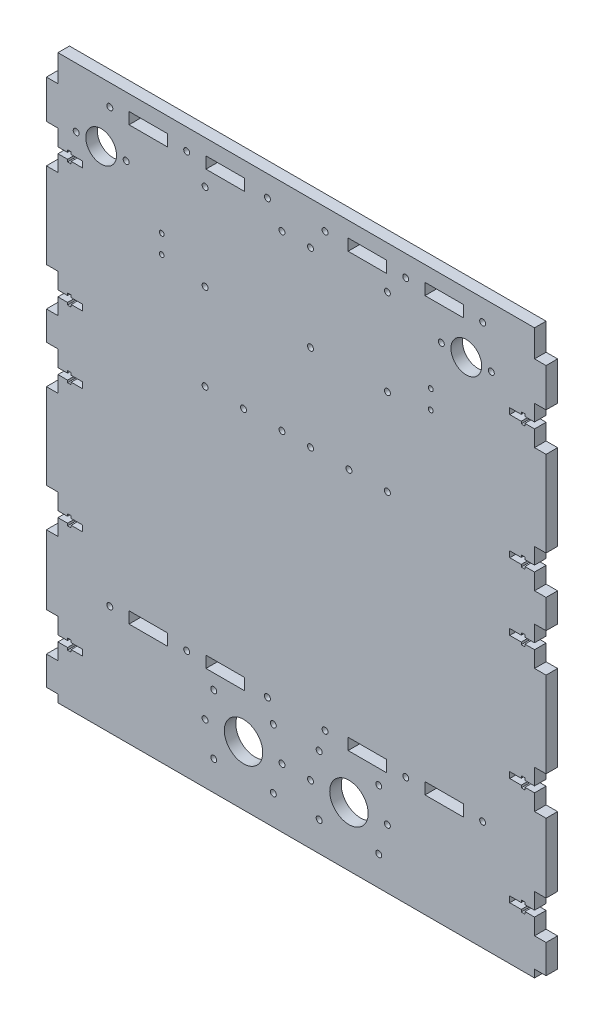
SolidWorks part; units mm, degrees
ref_plane "Front Plane" through (0, 0, 0) normal (0, 0, 1) x (1, 0, 0)
ref_plane "Top Plane" through (0, 0, 0) normal (0, 1, 0) x (1, 0, 0)
ref_plane "Right Plane" through (0, 0, 0) normal (1, 0, 0) x (0, 0, -1)
sketch "Sketch1" plane through (0, 0, 0) normal (0, 0, 1) x (1, 0, 0)
  line L1 (0, 0) -> (260, 0)
  line L2 (0, 0) -> (0, 270)
  line L3 (0, 270) -> (260, 270)
  line L4 (260, 0) -> (260, 270)
  dimension "D1" = 270
  dimension "D2" = 260
extrude "Boss-Extrude1" add sketch "Sketch1" along normal blind 6
sketch "Sketch2" plane through (0, 0, 0) normal (0, 0, -1) x (-1, 0, 0)
  line L0 (-130, 270) -> (-130, 0) construction
  line L1 (-217, 56) -> (-197, 56)
  line L2 (-217, 56) -> (-217, 50)
  line L3 (-217, 50) -> (-197, 50)
  line L4 (-197, 56) -> (-197, 50)
  line L5 (-177, 56) -> (-157, 56)
  line L6 (-177, 56) -> (-177, 50)
  line L7 (-177, 50) -> (-157, 50)
  line L8 (-157, 56) -> (-157, 50)
  line L9 (-260, 270) -> (0, 270) construction
  line L10 (0, 0) -> (-260, 0) construction
  line L11 (-260, 0) -> (-260, 270) construction
  line L12 (-217, 53) -> (-157, 53) construction
  line L13 (-130, 0) -> (-130, -73.8705) construction
  line L14 (-130, -73.8705) -> (-130, -196.098) construction
  line L16 (-220, 0) -> (-40, 0)
  line L17 (-83, 50) -> (-103, 50)
  line L18 (-103, 56) -> (-103, 50)
  line L19 (-83, 56) -> (-103, 56)
  line L20 (-83, 56) -> (-83, 50)
  line L21 (-43, 50) -> (-63, 50)
  line L22 (-63, 56) -> (-63, 50)
  line L23 (-43, 56) -> (-63, 56)
  line L24 (-43, 56) -> (-43, 50)
  arc A0 (-220, 0) -> (-40, 0) centre (-130, -400) cw
  point P23 (-130, 10)
  point P26 (-130, 10)
  dimension "D9" = 40
  dimension "D1" = 43
  dimension "D2" = 20
  dimension "D3" = 20
  dimension "D4" = 20
  dimension "D5" = 6
  dimension "D6" = 6
  dimension "D7" = 50
  dimension "D8" = 3
  dimension "D12" = 10
extrude "Cut-Extrude1" cut sketch "Sketch2" against normal blind 6
sketch "Sketch3" plane through (0, 0, 0) normal (0, 0, -1) x (-1, 0, 0)
  line L2 (-260, 255) -> (-260, 235)
  line L4 (-254, 255) -> (-254, 235)
  line L5 (-197, 56) -> (-217, 56) construction
  line L6 (-260, 255) -> (-254, 255)
  line L7 (-260, 255) -> (-260, 235)
  line L8 (-260, 235) -> (-254, 235)
  line L9 (-254, 255) -> (-254, 235)
  line L10 (-260, 190.5) -> (-254, 190.5)
  line L11 (-260, 190.5) -> (-260, 170.5)
  line L12 (-260, 170.5) -> (-254, 170.5)
  line L13 (-254, 190.5) -> (-254, 170.5)
  line L14 (-254, 155.5) -> (-260, 155.5)
  line L15 (-254, 155.5) -> (-254, 135.5)
  line L16 (-254, 135.5) -> (-260, 135.5)
  line L17 (-260, 155.5) -> (-260, 135.5)
  line L18 (-260, 91) -> (-254, 91)
  line L19 (-260, 91) -> (-260, 71)
  line L20 (-260, 71) -> (-254, 71)
  line L21 (-254, 91) -> (-254, 71)
  line L22 (-260, 35) -> (-254, 35)
  line L23 (-260, 35) -> (-260, 15)
  line L24 (-260, 15) -> (-254, 15)
  line L25 (-254, 35) -> (-254, 15)
  line L27 (-254, 190.5) -> (-254, 170.5)
  line L28 (-260, 190.5) -> (-260, 170.5)
  line L29 (-260, 155.5) -> (-260, 135.5)
  line L30 (-254, 155.5) -> (-254, 135.5)
  line L31 (-254, 91) -> (-254, 71)
  line L32 (-260, 91) -> (-260, 71)
  line L33 (-260, 35) -> (-260, 15)
  line L34 (-254, 35) -> (-254, 15)
  line L35 (-254, 270) -> (-254, 0) construction
  line L36 (-260, 270) -> (0, 270) construction
  line L37 (-220, 0) -> (-260, 0) construction
  line L38 (-260, 0) -> (-260, 270) construction
  line L39 (-130, 270) -> (-130, 0) construction
  line L40 (0, 15) -> (-6, 15)
  line L41 (-6, 35) -> (-6, 15)
  line L42 (0, 35) -> (-6, 35)
  line L43 (0, 35) -> (0, 15)
  line L44 (0, 71) -> (-6, 71)
  line L45 (-6, 91) -> (-6, 71)
  line L46 (0, 91) -> (-6, 91)
  line L47 (0, 91) -> (0, 71)
  line L48 (-6, 135.5) -> (0, 135.5)
  line L49 (0, 155.5) -> (0, 135.5)
  line L50 (-6, 155.5) -> (0, 155.5)
  line L51 (-6, 155.5) -> (-6, 135.5)
  line L52 (0, 170.5) -> (-6, 170.5)
  line L53 (-6, 190.5) -> (-6, 170.5)
  line L54 (0, 190.5) -> (-6, 190.5)
  line L55 (0, 190.5) -> (0, 170.5)
  line L56 (0, 235) -> (-6, 235)
  line L57 (-6, 255) -> (-6, 235)
  line L58 (0, 255) -> (-6, 255)
  line L59 (0, 255) -> (0, 235)
  point P27 (-257, 170.5)
  point P28 (-257, 155.5)
  point P29 (-257, 71)
  line M33 (0, 0) -> (0, 270)
  line M35 (-260, 270) -> (-260, 0)
  dimension "D1" = 6
  dimension "D2" = 20
  dimension "D3" = 20
  dimension "D4" = 20
  dimension "D5" = 20
  dimension "D6" = 20
  dimension "D7" = 6
  dimension "D8" = 15
  dimension "D9" = 44.5
  dimension "D10" = 15
  dimension "D11" = 44.5
extrude "Cut-Extrude2" cut sketch "Sketch3" against normal blind 10 contours L8 L4 L6 M35 | L13 L10 L12 M35 | L16 L15 L14 M35 | L21 L18 L20 M35 | L25 L22 L24 M35 | L42 L41 L40 M33 | L50 L51 L48 M33 | L54 L53 L52 M33 | L58 L57 L56 M33 | L47 L44 L45 L46
sketch "Sketch4" plane through (0, 0, 6) normal (0, 0, 1) x (1, 0, 0)
  line L0 (130, 270) -> (130, 0) construction
  line L1 (260, 270) -> (0, 270) construction
  line L2 (0, 270) -> (0, 255) construction
  line L3 (260, 270) -> (0, 270) construction
  circle A0 centre (28.5, 258) radius 8
  circle A2 centre (218.5, 258) radius 8
  dimension "D1" = 16
  dimension "D4" = 16
  dimension "D2" = 12
  dimension "D3" = 28.5
  dimension "D5" = 190
  dimension "D6" = 12
extrude "Cut-Extrude3" cut sketch "Sketch4" against normal blind 10
sketch "Sketch5" plane through (0, 0, 6) normal (0, 0, 1) x (1, 0, 0)
  line L0 (28.5, 266) -> (28.5, 250) construction
  line L1 (15.5, 258) -> (28.5, 258) construction
  line L2 (130, 270) -> (130, 307.8731) construction
  line L3 (260, 270) -> (0, 270) construction
  line L4 (205.5, 258) -> (231.5, 258) construction
  circle A0 centre (28.5, 258) radius 8 construction
  circle A1 centre (28.5, 258) radius 8
  circle A2 centre (15.5, 258) radius 1.55
  circle A3 centre (41.5, 258) radius 1.55
  circle A7 centre (218.5, 258) radius 8 construction
  circle A8 centre (218.5, 258) radius 8
  circle A9 centre (205.5, 258) radius 1.55
  circle A10 centre (231.5, 258) radius 1.55
  dimension "D2" = 3.1
  dimension "D3" = 3.1
  dimension "D4" = 13
  dimension "D7" = 3.1
  dimension "D1" = 13
  dimension "D5" = 13
  dimension "D6" = 13
extrude "Cut-Extrude4" cut sketch "Sketch5" against normal blind 6
sketch "Sketch6" plane through (0, 270, 0) normal (0, 1, 0) x (1, 0, 0)
  line L4 (260, 0) -> (0, 0)
  line L5 (0, 0) -> (0, -6)
  line L6 (0, -6) -> (260, -6)
  line L7 (260, -6) -> (260, 0)
  line L8 (260, 0) -> (0, 0)
  line L9 (0, 0) -> (0, -6)
  line L10 (0, -6) -> (260, -6)
  line L11 (260, -6) -> (260, 0)
  dimension "D1" = 0
extrude "Boss-Extrude2" add sketch "Sketch6" along normal blind 5
sketch "Sketch8" plane through (0, 0, 6) normal (0, 0, 1) x (1, 0, 0)
  line L0 (130, 137.5) -> (99.5396, 137.5) construction
  line L1 (0, 275) -> (260, 275) construction
  line L2 (0, 163) -> (24.6988, 163) construction
  line L3 (12.9, 243.45) -> (12.9, 242.25)
  line L4 (0, 170.5) -> (0, 155.5) construction
  line L5 (12.9, 243.45) -> (18.9, 243.45)
  line L6 (0, 113.25) -> (22.1113, 113.25) construction
  line L7 (0, 135.5) -> (0, 91) construction
  line L8 (0, 53) -> (19.2315, 53) construction
  line L9 (0, 71) -> (0, 35) construction
  line L34 (130, 275) -> (130, 0) construction
  line L35 (0, 212.75) -> (26.3273, 212.75) construction
  line L36 (0, 235) -> (0, 190.5) construction
  line L37 (6, 255) -> (6, 235) construction
  line L38 (6, 246.55) -> (11, 246.55)
  line L39 (6, 246.55) -> (6, 243.45)
  line L40 (6, 243.45) -> (11, 243.45)
  line L41 (18.9, 246.55) -> (18.9, 243.45)
  line L42 (6, 245) -> (35.7835, 245) construction
  line L43 (12.9, 246.55) -> (18.9, 246.55)
  line L44 (0, 255) -> (6, 255) construction
  line L45 (11, 243.45) -> (11, 242.25)
  line L46 (11, 247.75) -> (12.9, 247.75)
  line L47 (11, 247.75) -> (11, 246.55)
  line L48 (11, 242.25) -> (12.9, 242.25)
  line L49 (12.9, 247.75) -> (12.9, 246.55)
  line L50 (12.9, 177.75) -> (12.9, 178.95)
  line L51 (11, 183.25) -> (12.9, 183.25)
  line L52 (11, 177.75) -> (11, 178.95)
  line L53 (11, 177.75) -> (12.9, 177.75)
  line L54 (11, 182.05) -> (11, 183.25)
  line L55 (12.9, 178.95) -> (18.9, 178.95)
  line L56 (18.9, 178.95) -> (18.9, 182.05)
  line L57 (6, 182.05) -> (11, 182.05)
  line L58 (6, 178.95) -> (6, 182.05)
  line L59 (6, 178.95) -> (11, 178.95)
  line L60 (12.9, 182.05) -> (18.9, 182.05)
  line L61 (12.9, 182.05) -> (12.9, 183.25)
  line L62 (12.9, 143.95) -> (12.9, 142.75)
  line L63 (12.9, 143.95) -> (18.9, 143.95)
  line L64 (6, 147.05) -> (11, 147.05)
  line L65 (6, 147.05) -> (6, 143.95)
  line L66 (6, 143.95) -> (11, 143.95)
  line L67 (18.9, 147.05) -> (18.9, 143.95)
  line L68 (12.9, 147.05) -> (18.9, 147.05)
  line L69 (11, 143.95) -> (11, 142.75)
  line L70 (11, 148.25) -> (12.9, 148.25)
  line L71 (11, 148.25) -> (11, 147.05)
  line L72 (11, 142.75) -> (12.9, 142.75)
  line L73 (12.9, 148.25) -> (12.9, 147.05)
  line L74 (12.9, 78.25) -> (12.9, 79.45)
  line L75 (11, 83.75) -> (12.9, 83.75)
  line L76 (11, 78.25) -> (11, 79.45)
  line L77 (11, 78.25) -> (12.9, 78.25)
  line L78 (11, 82.55) -> (11, 83.75)
  line L79 (12.9, 79.45) -> (18.9, 79.45)
  line L80 (18.9, 79.45) -> (18.9, 82.55)
  line L81 (6, 82.55) -> (11, 82.55)
  line L82 (6, 79.45) -> (6, 82.55)
  line L83 (6, 79.45) -> (11, 79.45)
  line L84 (12.9, 82.55) -> (18.9, 82.55)
  line L85 (12.9, 82.55) -> (12.9, 83.75)
  line L86 (12.9, 23.45) -> (12.9, 22.25)
  line L87 (12.9, 23.45) -> (18.9, 23.45)
  line L88 (6, 26.55) -> (11, 26.55)
  line L89 (6, 26.55) -> (6, 23.45)
  line L90 (6, 23.45) -> (11, 23.45)
  line L91 (18.9, 26.55) -> (18.9, 23.45)
  line L92 (12.9, 26.55) -> (18.9, 26.55)
  line L93 (11, 23.45) -> (11, 22.25)
  line L94 (11, 27.75) -> (12.9, 27.75)
  line L95 (11, 27.75) -> (11, 26.55)
  line L96 (11, 22.25) -> (12.9, 22.25)
  line L97 (12.9, 27.75) -> (12.9, 26.55)
  line L98 (254, 245) -> (224.2165, 245) construction
  line L99 (260, 212.75) -> (233.6727, 212.75) construction
  line L100 (260, 53) -> (240.7685, 53) construction
  line L101 (260, 113.25) -> (237.8887, 113.25) construction
  line L102 (260, 163) -> (235.3012, 163) construction
  line L103 (247.1, 27.75) -> (247.1, 26.55)
  line L104 (249, 22.25) -> (247.1, 22.25)
  line L105 (249, 27.75) -> (249, 26.55)
  line L106 (249, 27.75) -> (247.1, 27.75)
  line L107 (249, 23.45) -> (249, 22.25)
  line L108 (247.1, 26.55) -> (241.1, 26.55)
  line L109 (241.1, 26.55) -> (241.1, 23.45)
  line L110 (254, 23.45) -> (249, 23.45)
  line L111 (254, 26.55) -> (254, 23.45)
  line L112 (254, 26.55) -> (249, 26.55)
  line L113 (247.1, 23.45) -> (241.1, 23.45)
  line L114 (247.1, 23.45) -> (247.1, 22.25)
  line L115 (247.1, 82.55) -> (247.1, 83.75)
  line L116 (247.1, 82.55) -> (241.1, 82.55)
  line L117 (254, 79.45) -> (249, 79.45)
  line L118 (254, 79.45) -> (254, 82.55)
  line L119 (254, 82.55) -> (249, 82.55)
  line L120 (241.1, 79.45) -> (241.1, 82.55)
  line L121 (247.1, 79.45) -> (241.1, 79.45)
  line L122 (249, 82.55) -> (249, 83.75)
  line L123 (249, 78.25) -> (247.1, 78.25)
  line L124 (249, 78.25) -> (249, 79.45)
  line L125 (249, 83.75) -> (247.1, 83.75)
  line L126 (247.1, 78.25) -> (247.1, 79.45)
  line L127 (247.1, 148.25) -> (247.1, 147.05)
  line L128 (249, 142.75) -> (247.1, 142.75)
  line L129 (249, 148.25) -> (249, 147.05)
  line L130 (249, 148.25) -> (247.1, 148.25)
  line L131 (249, 143.95) -> (249, 142.75)
  line L132 (247.1, 147.05) -> (241.1, 147.05)
  line L133 (241.1, 147.05) -> (241.1, 143.95)
  line L134 (254, 143.95) -> (249, 143.95)
  line L135 (254, 147.05) -> (254, 143.95)
  line L136 (254, 147.05) -> (249, 147.05)
  line L137 (247.1, 143.95) -> (241.1, 143.95)
  line L138 (247.1, 143.95) -> (247.1, 142.75)
  line L139 (247.1, 182.05) -> (247.1, 183.25)
  line L140 (247.1, 182.05) -> (241.1, 182.05)
  line L141 (254, 178.95) -> (249, 178.95)
  line L142 (254, 178.95) -> (254, 182.05)
  line L143 (254, 182.05) -> (249, 182.05)
  line L144 (241.1, 178.95) -> (241.1, 182.05)
  line L145 (247.1, 178.95) -> (241.1, 178.95)
  line L146 (249, 182.05) -> (249, 183.25)
  line L147 (249, 177.75) -> (247.1, 177.75)
  line L148 (249, 177.75) -> (249, 178.95)
  line L149 (249, 183.25) -> (247.1, 183.25)
  line L150 (247.1, 177.75) -> (247.1, 178.95)
  line L151 (247.1, 247.75) -> (247.1, 246.55)
  line L152 (249, 242.25) -> (247.1, 242.25)
  line L153 (249, 247.75) -> (249, 246.55)
  line L154 (249, 247.75) -> (247.1, 247.75)
  line L155 (249, 243.45) -> (249, 242.25)
  line L156 (247.1, 246.55) -> (241.1, 246.55)
  line L157 (241.1, 246.55) -> (241.1, 243.45)
  line L158 (254, 243.45) -> (249, 243.45)
  line L159 (254, 246.55) -> (254, 243.45)
  line L160 (254, 246.55) -> (249, 246.55)
  line L161 (247.1, 243.45) -> (241.1, 243.45)
  line L162 (247.1, 243.45) -> (247.1, 242.25)
  dimension "D1" = 10
  dimension "D2" = 1.55
  dimension "D3" = 12.9
  dimension "D4" = 6
  dimension "D5" = 5
  dimension "D6" = 5.5
  dimension "D7" = 2.75
extrude "Cut-Extrude6" cut sketch "Sketch8" against normal blind 10
sketch "Sketch9" plane through (0, 0, 6) normal (0, 0, 1) x (1, 0, 0)
  line L0 (0, 53) -> (260, 53) construction
  line L1 (0, 71) -> (0, 35) construction
  line L2 (260, 35) -> (260, 71) construction
  line L3 (130, 53) -> (130, 64.3337) construction
  line L4 (43, 50) -> (43, 56) construction
  line L5 (63, 56) -> (63, 50) construction
  circle A0 centre (33, 53) radius 1.55
  circle A1 centre (73, 53) radius 1.55
  circle A2 centre (115, 53) radius 1.55
  circle A3 centre (145, 53) radius 1.55
  circle A4 centre (187, 53) radius 1.55
  circle A5 centre (227, 53) radius 1.55
  dimension "D1" = 3.1
  dimension "D2" = 15
  dimension "D3" = 3.1
  dimension "D4" = 3.1
  dimension "D5" = 10
  dimension "D6" = 10
extrude "Cut-Extrude7" cut sketch "Sketch9" against normal blind 10
sketch "Sketch11" plane through (0, 0, 0) normal (0, 0, 1) x (1, 0, 0)
  line L0 (157.4295, 5) -> (157.4295, 275) construction
  line L1 (157.4295, 5) -> (200, 5) construction
  line L2 (177.4295, 176.8379) -> (177.4295, 178.3879) construction
  line L3 (157.4295, 275) -> (200, 275) construction
  line L4 (157.4295, 176.8379) -> (157.4295, 178.55) construction
  line L5 (200, 5) -> (200, 275) construction
  line L6 (177.4295, 220.2879) -> (177.4295, 223.3879) construction
  line L7 (0, 275) -> (260, 275) construction
  line L8 (177.4302, 26.8379) -> (137.4288, 26.8379) construction
  line L10 (260, 35) -> (260, 71) construction
  line L12 (137.4295, 220.2879) -> (137.4295, 223.3879) construction
  line L13 (137.4295, 176.8379) -> (137.4295, 178.3879) construction
  line L14 (130, 275) -> (130, 282.4006) construction
  line L15 (260, 275) -> (0, 275) construction
  line L16 (122.5705, 176.8379) -> (122.5705, 178.3879) construction
  line L17 (122.5705, 220.2879) -> (122.5705, 223.3879) construction
  line L18 (82.5698, 26.8379) -> (122.5712, 26.8379) construction
  line L19 (82.5705, 220.2879) -> (82.5705, 223.3879) construction
  line L20 (60, 5) -> (60, 275) construction
  line L21 (102.5705, 176.8379) -> (102.5705, 178.55) construction
  line L22 (102.5705, 275) -> (60, 275) construction
  line L23 (82.5705, 176.8379) -> (82.5705, 178.3879) construction
  line L24 (102.5705, 5) -> (60, 5) construction
  line L25 (102.5705, 5) -> (102.5705, 275) construction
  line L26 (260, 255) -> (260, 275) construction
  circle A0 centre (177.4295, 221.8379) radius 1.55
  circle A1 centre (177.4295, 266.8379) radius 1.55
  circle A6 centre (157.4295, 26.8379) radius 10
  circle A7 centre (137.4288, 26.8379) radius 1.55
  circle A8 centre (141.9302, 42.3379) radius 1.55
  circle A9 centre (141.9302, 11.3379) radius 1.55
  circle A10 centre (172.9288, 11.3379) radius 1.55
  circle A14 centre (172.9288, 42.3379) radius 1.55
  circle A15 centre (177.4302, 26.8379) radius 1.55
  circle A17 centre (177.4295, 176.8379) radius 1.55
  circle A18 centre (157.4295, 176.8379) radius 1.55
  circle A20 centre (137.4295, 176.8379) radius 1.55
  circle A21 centre (137.4295, 266.8379) radius 1.55
  circle A22 centre (137.4295, 221.8379) radius 1.55
  circle A37 centre (122.5705, 221.8379) radius 1.55
  circle A38 centre (122.5705, 266.8379) radius 1.55
  circle A39 centre (122.5705, 176.8379) radius 1.55
  circle A40 centre (102.5705, 176.8379) radius 1.55
  circle A41 centre (82.5705, 176.8379) radius 1.55
  circle A42 centre (82.5698, 26.8379) radius 1.55
  circle A43 centre (87.0712, 42.3379) radius 1.55
  circle A44 centre (87.0712, 11.3379) radius 1.55
  circle A45 centre (118.0698, 11.3379) radius 1.55
  circle A46 centre (118.0698, 42.3379) radius 1.55
  circle A47 centre (122.5712, 26.8379) radius 1.55
  circle A48 centre (102.5705, 26.8379) radius 10
  circle A49 centre (82.5705, 266.8379) radius 1.55
  circle A50 centre (82.5705, 221.8379) radius 1.55
  dimension "D3" = 3.1
  dimension "D4" = 3.1
  dimension "D5" = 102.5705
  dimension "D6" = 20
  dimension "D7" = 270
  dimension "D8" = 40
  dimension "D9" = 31
  dimension "D10" = 8.1621
  dimension "D11" = 3.1
  dimension "D12" = 3.1
  dimension "D13" = 3.1
  dimension "D14" = 40.0013
  dimension "D15" = 15.4993
  dimension "D16" = 15.5
  dimension "D17" = 15.4993
  dimension "D18" = 60
  dimension "D21" = 45
  dimension "D23" = 3.1
  dimension "D28" = 3.1
  dimension "D19" = 150
  dimension "D22" = 45
  dimension "D20" = 20
sketch "Sketch12" plane through (0, 0, 0) normal (0, 0, 1) x (1, 0, 0)
  line L0 (130, 270) -> (130, 0) construction
  line L13 (130, 0) -> (130, -73.8705) construction
  line L14 (130, -73.8705) -> (130, -196.098) construction
  line L16 (40, 0) -> (220, 0)
  arc A0 (40, 0) -> (220, 0) centre (130, -400) cw
  point P23 (130, 10)
  point P26 (130, 10)
extrude "Boss-Extrude3" add sketch "Sketch12" along normal blind 6
extrude "Cut-Extrude9" cut sketch "Sketch11" along normal blind 10 contours A6 | A48
sketch "Sketch13" plane through (0, 275, 0) normal (0, 1, 0) x (1, 0, 0)
  line L0 (6, -6) -> (6, 0)
  line L1 (254, 0) -> (254, -6)
  line L2 (0, 0) -> (0, -6) construction
  line L4 (260, -6) -> (260, 0)
  line L5 (260, 0) -> (0, 0)
  line L6 (0, 0) -> (0, -6)
  line L7 (0, -6) -> (260, -6)
  line L9 (254, 0) -> (6, 0)
  line L11 (6, -6) -> (254, -6)
  dimension "D2" = 6
  dimension "D1" = 0
extrude "Boss-Extrude4" add sketch "Sketch13" along normal blind 14
sketch "Sketch14" plane through (0, 0, 0) normal (0, -1, 0) x (1, 0, 0)
  line L0 (6, 6) -> (6, 0)
  line L1 (254, 6) -> (254, 0)
  line L4 (0, 0) -> (260, 0)
  line L5 (260, 0) -> (260, 6)
  line L6 (260, 6) -> (0, 6)
  line L7 (0, 6) -> (0, 0)
  line L8 (6, 0) -> (254, 0)
  line L9 (260, 0) -> (260, 6)
  line L10 (254, 6) -> (6, 6)
  point P8 (260, 3)
  line M5 (0, 0) -> (260, 0)
  line M7 (260, 6) -> (0, 6)
  dimension "D2" = 6
  dimension "D3" = 6
  dimension "D1" = 0
extrude "Boss-Extrude5" add sketch "Sketch14" along normal blind 4 contours L1 L0 M7 M5
sketch "Sketch15" plane through (0, 0, 6) normal (0, 0, 1) x (1, 0, 0)
  line L0 (217, 56) -> (217, 50) construction
  line L1 (217, 50) -> (197, 50) construction
  line L2 (197, 56) -> (217, 56) construction
  line L3 (197, 50) -> (197, 56) construction
  line L4 (177, 50) -> (157, 50) construction
  line L5 (177, 56) -> (177, 50) construction
  line L6 (157, 56) -> (177, 56) construction
  line L7 (157, 50) -> (157, 56) construction
  line L8 (103, 50) -> (83, 50) construction
  line L9 (103, 56) -> (103, 50) construction
  line L10 (83, 56) -> (103, 56) construction
  line L11 (83, 50) -> (83, 56) construction
  line L12 (63, 56) -> (63, 50) construction
  line L13 (63, 50) -> (43, 50) construction
  line L14 (43, 50) -> (43, 56) construction
  line L15 (43, 56) -> (63, 56) construction
  line L16 (217, 56) -> (217, 50)
  line L17 (217, 50) -> (197, 50)
  line L18 (197, 56) -> (217, 56)
  line L19 (197, 50) -> (197, 56)
  line L20 (177, 50) -> (157, 50)
  line L21 (177, 56) -> (177, 50)
  line L22 (157, 56) -> (177, 56)
  line L23 (157, 50) -> (157, 56)
  line L24 (103, 50) -> (83, 50)
  line L25 (103, 56) -> (103, 50)
  line L26 (83, 56) -> (103, 56)
  line L27 (83, 50) -> (83, 56)
  line L28 (63, 56) -> (63, 50)
  line L29 (63, 50) -> (43, 50)
  line L30 (43, 50) -> (43, 56)
  line L31 (43, 56) -> (63, 56)
  line L32 (63, 281) -> (63, 275)
  line L33 (63, 275) -> (43, 275)
  line L34 (43, 275) -> (43, 281)
  line L35 (43, 281) -> (63, 281)
  line L36 (103, 275) -> (83, 275)
  line L37 (83, 275) -> (83, 281)
  line L38 (83, 281) -> (103, 281)
  line L39 (103, 281) -> (103, 275)
  line L40 (177, 275) -> (157, 275)
  line L41 (157, 275) -> (157, 281)
  line L42 (157, 281) -> (177, 281)
  line L43 (177, 281) -> (177, 275)
  line L44 (217, 281) -> (217, 275)
  line L45 (217, 275) -> (197, 275)
  line L46 (197, 275) -> (197, 281)
  line L47 (197, 281) -> (217, 281)
  circle A0 centre (227, 53) radius 1.55 construction
  circle A1 centre (187, 53) radius 1.55 construction
  circle A2 centre (145, 53) radius 1.55 construction
  circle A3 centre (115, 53) radius 1.55 construction
  circle A4 centre (73, 53) radius 1.55 construction
  circle A5 centre (33, 53) radius 1.55 construction
  circle A6 centre (227, 53) radius 1.55
  circle A7 centre (187, 53) radius 1.55
  circle A8 centre (145, 53) radius 1.55
  circle A9 centre (115, 53) radius 1.55
  circle A10 centre (73, 53) radius 1.55
  circle A11 centre (33, 53) radius 1.55
  circle A12 centre (33, 278) radius 1.55
  circle A13 centre (73, 278) radius 1.55
  circle A14 centre (115, 278) radius 1.55
  circle A15 centre (145, 278) radius 1.55
  circle A16 centre (187, 278) radius 1.55
  circle A17 centre (227, 278) radius 1.55
  dimension "D2" = 225
  dimension "D1" = 2
extrude "Cut-Extrude10" cut sketch "Sketch15" against normal blind 10
sketch "Sketch16" plane through (0, 0, 6) normal (0, 0, 1) x (1, 0, 0)
  line L0 (60, 327.3562) -> (60, 187.4877) construction
  line L1 (0, 235) -> (0, 190.5) construction
  line L2 (27.6338, 225) -> (208.8135, 225) construction
  line L3 (6, 289) -> (254, 289) construction
  line L4 (130, 289) -> (130, 298.7127) construction
  line L5 (232.3662, 225) -> (51.1865, 225) construction
  line L6 (200, 327.3562) -> (200, 187.4877) construction
  circle A0 centre (60, 225) radius 1.25
  circle A1 centre (60, 234.6) radius 1.25
  circle A2 centre (200, 234.6) radius 1.25
  circle A3 centre (200, 225) radius 1.25
  point P8 (60, 225)
  dimension "D3" = 2.5
  dimension "D4" = 2.5
  dimension "D5" = 9.6
  dimension "D1" = 60
  dimension "D2" = 64
extrude "Cut-Extrude11" cut sketch "Sketch16" against normal blind 10
